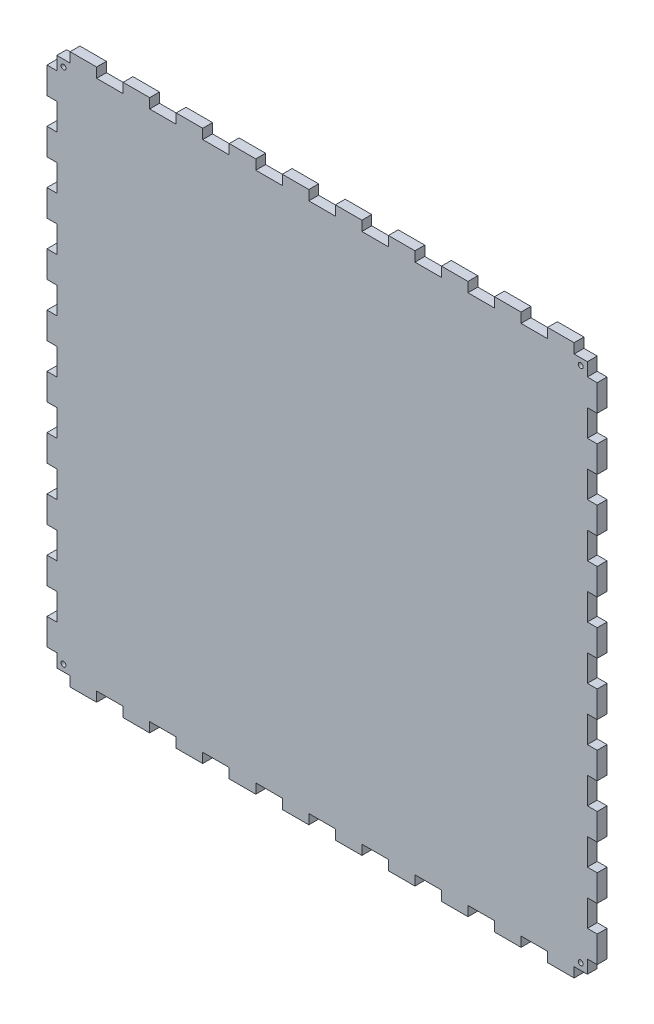
SolidWorks part; units mm, degrees
ref_plane "Front Plane" through (0, 0, 0) normal (0, 0, 1) x (1, 0, 0)
ref_plane "Top Plane" through (0, 0, 0) normal (0, 1, 0) x (1, 0, 0)
ref_plane "Right Plane" through (0, 0, 0) normal (1, 0, 0) x (0, 0, -1)
sketch "Sketch1" plane through (0, 0, 0) normal (0, 0, 1) x (1, 0, 0)
  line L0 (6.35, 349.25) -> (6.35, 6.35) construction
  line L1 (0, 0) -> (355.6, 0) construction
  line L2 (0, 0) -> (0, 355.6) construction
  line L3 (0, 355.6) -> (355.6, 355.6) construction
  line L4 (355.6, 0) -> (355.6, 355.6) construction
  line L5 (0, 6.35) -> (349.25, 6.35) construction
  line L6 (0, 349.25) -> (349.25, 349.25) construction
  line L7 (349.25, 349.25) -> (349.25, 0) construction
  line L8 (6.35, 349.25) -> (14.9225, 349.25)
  line L9 (14.9225, 349.25) -> (14.9225, 355.6)
  line L10 (14.9225, 355.6) -> (32.0675, 355.6)
  line L11 (32.0675, 355.6) -> (32.0675, 349.25)
  line L12 (32.0675, 349.25) -> (49.2125, 349.25)
  line L13 (14.9225, 355.6) -> (32.0675, 355.6)
  line L14 (66.3575, 349.25) -> (83.5025, 349.25)
  line L15 (66.3575, 355.6) -> (66.3575, 349.25)
  line L16 (49.2125, 355.6) -> (66.3575, 355.6)
  line L17 (49.2125, 349.25) -> (49.2125, 355.6)
  line L18 (100.6475, 349.25) -> (117.7925, 349.25)
  line L19 (100.6475, 355.6) -> (100.6475, 349.25)
  line L20 (83.5025, 355.6) -> (100.6475, 355.6)
  line L21 (83.5025, 349.25) -> (83.5025, 355.6)
  line L22 (134.9375, 349.25) -> (152.0825, 349.25)
  line L23 (134.9375, 355.6) -> (134.9375, 349.25)
  line L24 (117.7925, 355.6) -> (134.9375, 355.6)
  line L25 (117.7925, 349.25) -> (117.7925, 355.6)
  line L26 (169.2275, 349.25) -> (186.3725, 349.25)
  line L27 (169.2275, 355.6) -> (169.2275, 349.25)
  line L28 (152.0825, 355.6) -> (169.2275, 355.6)
  line L29 (152.0825, 349.25) -> (152.0825, 355.6)
  line L30 (203.5175, 349.25) -> (220.6625, 349.25)
  line L31 (203.5175, 355.6) -> (203.5175, 349.25)
  line L32 (186.3725, 355.6) -> (203.5175, 355.6)
  line L33 (186.3725, 349.25) -> (186.3725, 355.6)
  line L34 (237.8075, 349.25) -> (254.9525, 349.25)
  line L35 (237.8075, 355.6) -> (237.8075, 349.25)
  line L36 (220.6625, 355.6) -> (237.8075, 355.6)
  line L37 (220.6625, 349.25) -> (220.6625, 355.6)
  line L38 (272.0975, 349.25) -> (289.2425, 349.25)
  line L39 (272.0975, 355.6) -> (272.0975, 349.25)
  line L40 (254.9525, 355.6) -> (272.0975, 355.6)
  line L41 (254.9525, 349.25) -> (254.9525, 355.6)
  line L42 (306.3875, 349.25) -> (323.5325, 349.25)
  line L43 (306.3875, 355.6) -> (306.3875, 349.25)
  line L44 (289.2425, 355.6) -> (306.3875, 355.6)
  line L45 (289.2425, 349.25) -> (289.2425, 355.6)
  line L46 (340.6775, 349.25) -> (349.25, 349.25)
  line L47 (340.6775, 355.6) -> (340.6775, 349.25)
  line L48 (323.5325, 355.6) -> (340.6775, 355.6)
  line L49 (323.5325, 349.25) -> (323.5325, 355.6)
  line L50 (6.35, 349.25) -> (6.35, 340.6775)
  line L51 (6.35, 340.6775) -> (0, 340.6775)
  line L52 (0, 340.6775) -> (0, 323.5325)
  line L53 (0, 323.5325) -> (6.35, 323.5325)
  line L54 (6.35, 323.5325) -> (6.35, 306.3875)
  line L55 (6.35, 289.2425) -> (6.35, 272.0975)
  line L56 (0, 289.2425) -> (6.35, 289.2425)
  line L57 (0, 306.3875) -> (0, 289.2425)
  line L58 (6.35, 306.3875) -> (0, 306.3875)
  line L59 (6.35, 254.9525) -> (6.35, 237.8075)
  line L60 (0, 254.9525) -> (6.35, 254.9525)
  line L61 (0, 272.0975) -> (0, 254.9525)
  line L62 (6.35, 272.0975) -> (0, 272.0975)
  line L63 (6.35, 220.6625) -> (6.35, 203.5175)
  line L64 (0, 220.6625) -> (6.35, 220.6625)
  line L65 (0, 237.8075) -> (0, 220.6625)
  line L66 (6.35, 237.8075) -> (0, 237.8075)
  line L67 (6.35, 186.3725) -> (6.35, 169.2275)
  line L68 (0, 186.3725) -> (6.35, 186.3725)
  line L69 (0, 203.5175) -> (0, 186.3725)
  line L70 (6.35, 203.5175) -> (0, 203.5175)
  line L71 (6.35, 152.0825) -> (6.35, 134.9375)
  line L72 (0, 152.0825) -> (6.35, 152.0825)
  line L73 (0, 169.2275) -> (0, 152.0825)
  line L74 (6.35, 169.2275) -> (0, 169.2275)
  line L75 (6.35, 117.7925) -> (6.35, 100.6475)
  line L76 (0, 117.7925) -> (6.35, 117.7925)
  line L77 (0, 134.9375) -> (0, 117.7925)
  line L78 (6.35, 134.9375) -> (0, 134.9375)
  line L79 (6.35, 83.5025) -> (6.35, 66.3575)
  line L80 (0, 83.5025) -> (6.35, 83.5025)
  line L81 (0, 100.6475) -> (0, 83.5025)
  line L82 (6.35, 100.6475) -> (0, 100.6475)
  line L83 (6.35, 49.2125) -> (6.35, 32.0675)
  line L84 (0, 49.2125) -> (6.35, 49.2125)
  line L85 (0, 66.3575) -> (0, 49.2125)
  line L86 (6.35, 66.3575) -> (0, 66.3575)
  line L87 (6.35, 14.9225) -> (6.35, 6.35)
  line L88 (0, 14.9225) -> (6.35, 14.9225)
  line L89 (0, 32.0675) -> (0, 14.9225)
  line L90 (6.35, 32.0675) -> (0, 32.0675)
  line L91 (6.35, 6.35) -> (14.9225, 6.35)
  line L92 (14.9225, 6.35) -> (14.9225, 0)
  line L93 (14.9225, 0) -> (32.0675, 0)
  line L94 (32.0675, 0) -> (32.0675, 6.35)
  line L95 (32.0675, 6.35) -> (49.2125, 6.35)
  line L96 (66.3575, 6.35) -> (83.5025, 6.35)
  line L97 (66.3575, 0) -> (66.3575, 6.35)
  line L98 (49.2125, 0) -> (66.3575, 0)
  line L99 (49.2125, 6.35) -> (49.2125, 0)
  line L100 (100.6475, 6.35) -> (117.7925, 6.35)
  line L101 (100.6475, 0) -> (100.6475, 6.35)
  line L102 (83.5025, 0) -> (100.6475, 0)
  line L103 (83.5025, 6.35) -> (83.5025, 0)
  line L104 (134.9375, 6.35) -> (152.0825, 6.35)
  line L105 (134.9375, 0) -> (134.9375, 6.35)
  line L106 (117.7925, 0) -> (134.9375, 0)
  line L107 (117.7925, 6.35) -> (117.7925, 0)
  line L108 (169.2275, 6.35) -> (186.3725, 6.35)
  line L109 (169.2275, 0) -> (169.2275, 6.35)
  line L110 (152.0825, 0) -> (169.2275, 0)
  line L111 (152.0825, 6.35) -> (152.0825, 0)
  line L112 (203.5175, 6.35) -> (220.6625, 6.35)
  line L113 (203.5175, 0) -> (203.5175, 6.35)
  line L114 (186.3725, 0) -> (203.5175, 0)
  line L115 (186.3725, 6.35) -> (186.3725, 0)
  line L116 (237.8075, 6.35) -> (254.9525, 6.35)
  line L117 (237.8075, 0) -> (237.8075, 6.35)
  line L118 (220.6625, 0) -> (237.8075, 0)
  line L119 (220.6625, 6.35) -> (220.6625, 0)
  line L120 (272.0975, 6.35) -> (289.2425, 6.35)
  line L121 (272.0975, 0) -> (272.0975, 6.35)
  line L122 (254.9525, 0) -> (272.0975, 0)
  line L123 (254.9525, 6.35) -> (254.9525, 0)
  line L124 (306.3875, 6.35) -> (323.5325, 6.35)
  line L125 (306.3875, 0) -> (306.3875, 6.35)
  line L126 (289.2425, 0) -> (306.3875, 0)
  line L127 (289.2425, 6.35) -> (289.2425, 0)
  line L128 (340.6775, 6.35) -> (349.25, 6.35)
  line L129 (340.6775, 0) -> (340.6775, 6.35)
  line L130 (323.5325, 0) -> (340.6775, 0)
  line L131 (323.5325, 6.35) -> (323.5325, 0)
  line L132 (349.25, 6.35) -> (349.25, 14.9225)
  line L133 (349.25, 14.9225) -> (355.6, 14.9225)
  line L134 (355.6, 14.9225) -> (355.6, 32.0675)
  line L135 (355.6, 32.0675) -> (349.25, 32.0675)
  line L136 (349.25, 32.0675) -> (349.25, 49.2125)
  line L137 (349.25, 66.3575) -> (349.25, 83.5025)
  line L138 (355.6, 66.3575) -> (349.25, 66.3575)
  line L139 (355.6, 49.2125) -> (355.6, 66.3575)
  line L140 (349.25, 49.2125) -> (355.6, 49.2125)
  line L141 (349.25, 100.6475) -> (349.25, 117.7925)
  line L142 (355.6, 100.6475) -> (349.25, 100.6475)
  line L143 (355.6, 83.5025) -> (355.6, 100.6475)
  line L144 (349.25, 83.5025) -> (355.6, 83.5025)
  line L145 (349.25, 134.9375) -> (349.25, 152.0825)
  line L146 (355.6, 134.9375) -> (349.25, 134.9375)
  line L147 (355.6, 117.7925) -> (355.6, 134.9375)
  line L148 (349.25, 117.7925) -> (355.6, 117.7925)
  line L149 (349.25, 169.2275) -> (349.25, 186.3725)
  line L150 (355.6, 169.2275) -> (349.25, 169.2275)
  line L151 (355.6, 152.0825) -> (355.6, 169.2275)
  line L152 (349.25, 152.0825) -> (355.6, 152.0825)
  line L153 (349.25, 203.5175) -> (349.25, 220.6625)
  line L154 (355.6, 203.5175) -> (349.25, 203.5175)
  line L155 (355.6, 186.3725) -> (355.6, 203.5175)
  line L156 (349.25, 186.3725) -> (355.6, 186.3725)
  line L157 (349.25, 237.8075) -> (349.25, 254.9525)
  line L158 (355.6, 237.8075) -> (349.25, 237.8075)
  line L159 (355.6, 220.6625) -> (355.6, 237.8075)
  line L160 (349.25, 220.6625) -> (355.6, 220.6625)
  line L161 (349.25, 272.0975) -> (349.25, 289.2425)
  line L162 (355.6, 272.0975) -> (349.25, 272.0975)
  line L163 (355.6, 254.9525) -> (355.6, 272.0975)
  line L164 (349.25, 254.9525) -> (355.6, 254.9525)
  line L165 (349.25, 306.3875) -> (349.25, 323.5325)
  line L166 (355.6, 306.3875) -> (349.25, 306.3875)
  line L167 (355.6, 289.2425) -> (355.6, 306.3875)
  line L168 (349.25, 289.2425) -> (355.6, 289.2425)
  line L169 (349.25, 340.6775) -> (349.25, 349.25)
  line L170 (355.6, 340.6775) -> (349.25, 340.6775)
  line L171 (355.6, 323.5325) -> (355.6, 340.6775)
  line L172 (349.25, 323.5325) -> (355.6, 323.5325)
  line L173 (177.8, 349.25) -> (177.8, -49650.75) construction
  line L174 (6.35, 177.8) -> (50006.35, 177.8) construction
  circle A0 centre (10.668, 344.932) radius 1.5875
  circle A1 centre (344.932, 344.932) radius 1.5875
  circle A2 centre (344.932, 10.668) radius 1.5875
  circle A3 centre (10.668, 10.668) radius 1.5875
  point P154 (177.8, 349.25)
  point P159 (177.8, 6.35)
  point P174 (6.35, 177.8)
  point P179 (349.25, 177.8)
  dimension "D13" = 4.318
  dimension "D1" = 355.6
  dimension "D2" = 355.6
  dimension "D3" = 6.35
  dimension "D4" = 6.35
  dimension "D5" = 10
  dimension "D6" = 6.35
  dimension "D7" = 8.5725
  dimension "D8" = 17.145
  dimension "D9" = 17.145
  dimension "D10" = 10
  dimension "D11" = 10
  dimension "D14" = 4.318
  dimension "D12" = 10
extrude "Boss-Extrude1" add sketch "Sketch1" along normal blind 6.35 contours L165 L172 L171 L170 L169 L46 L47 L48 L49 L42 L43 L44 L45 L38 L39 L40 L41 L34 L35 L36 L37 L30 L31 L32 L33 L26 L27 L28 L29 L22 L23 L24 L25 L18 L19 L20 L21 L14 L15 L16 L17 L12 L11 L10 L9 L8 L50 L51 L52 L53 L54
